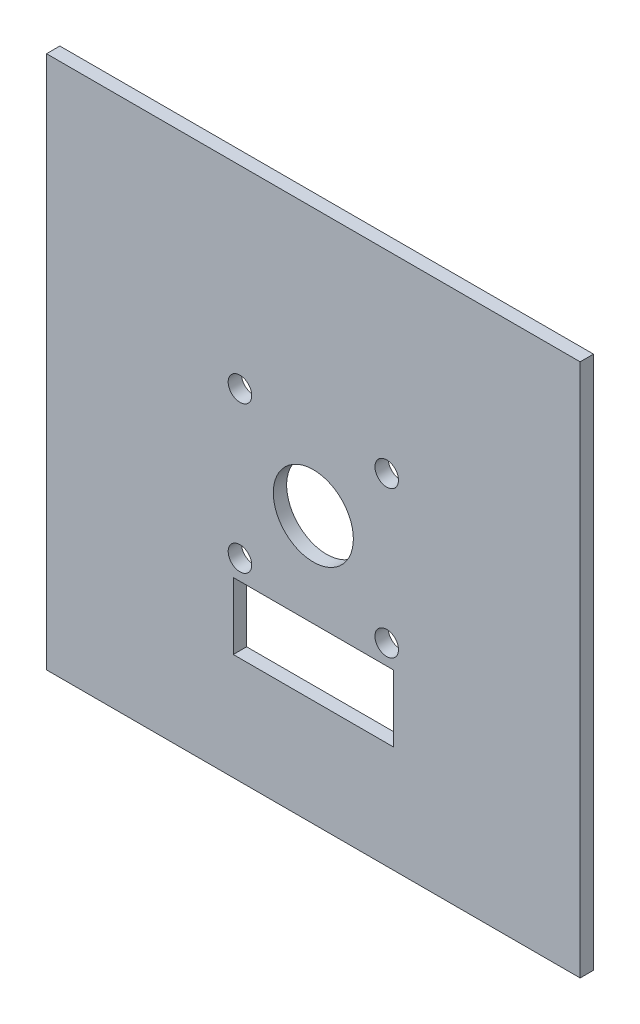
SolidWorks part; units mm, degrees
ref_plane "Front Plane" through (0, 0, 0) normal (0, 0, 1) x (1, 0, 0)
ref_plane "Top Plane" through (0, 0, 0) normal (0, 1, 0) x (1, 0, 0)
ref_plane "Right Plane" through (0, 0, 0) normal (1, 0, 0) x (0, 0, -1)
sketch "Sketch1" plane through (0, 0, 0) normal (0, 0, 1) x (1, 0, 0)
  line L0 (-259.5239, 0) -> (259.5239, 0) construction
  line L1 (0, -214.3934) -> (0, 214.3934) construction
  line L3 (-127, -127) -> (127, -127)
  line L4 (-127, -127) -> (-127, 127)
  line L5 (-127, 127) -> (127, 127)
  line L6 (127, -127) -> (127, 127)
  line L7 (-127, -127) -> (127, 127) construction
  line L8 (-127, 127) -> (127, -127) construction
  line L9 (-38.1, -76.2) -> (38.1, -76.2)
  line L10 (-38.1, -76.2) -> (-38.1, -44.45)
  line L11 (-38.1, -44.45) -> (38.1, -44.45)
  line L12 (38.1, -76.2) -> (38.1, -44.45)
  line L13 (-38.1, -76.2) -> (38.1, -44.45) construction
  line L14 (-38.1, -44.45) -> (38.1, -76.2) construction
  line L19 (-47.625, -47.625) -> (47.625, 47.625) construction
  line L20 (-47.625, 47.625) -> (47.625, -47.625) construction
  circle A0 centre (0, 0) radius 19.05
  circle A1 centre (-34.925, 34.925) radius 5.6031
  circle A2 centre (34.925, 34.925) radius 5.6031
  circle A3 centre (34.925, -34.925) radius 5.6031
  circle A4 centre (-34.925, -34.925) radius 5.6031
  point P0 (0, 0)
  point P4 (0, 0)
  point P8 (0, 0)
  point P15 (0, -60.325)
  dimension "D3" = 38.1
  dimension "D1" = 254
  dimension "D2" = 254
  dimension "D4" = 50.8
  dimension "D5" = 76.2
  dimension "D6" = 31.75
  dimension "D7" = 95.25
  dimension "D8" = 95.25
  dimension "D9" = 34.925
  dimension "D10" = 34.925
extrude "Boss-Extrude1" add sketch "Sketch1" along normal mid plane 6.35 contours L3 L6 L5 L4 A0 A1 A2 L10 A4 L11 A3 L12 L9
